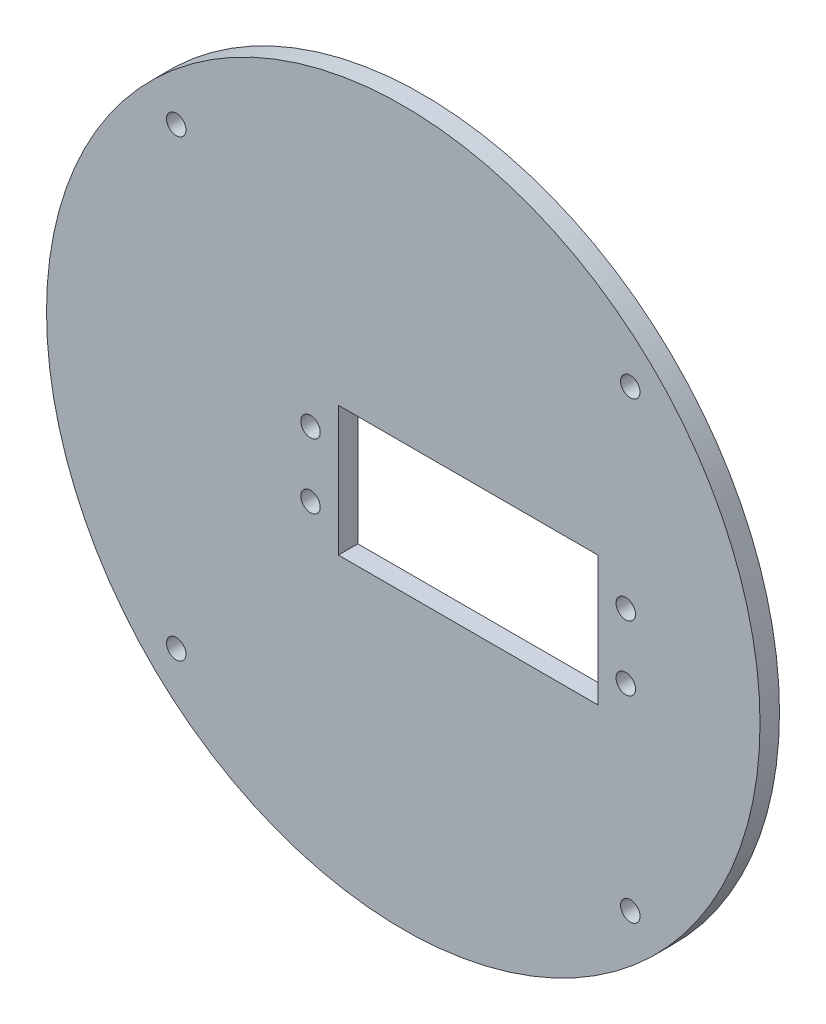
SolidWorks part; units mm, degrees
ref_plane "前视基准面" through (0, 0, 0) normal (0, 0, 1) x (1, 0, 0)
ref_plane "上视基准面" through (0, 0, 0) normal (0, 1, 0) x (1, 0, 0)
ref_plane "右视基准面" through (0, 0, 0) normal (1, 0, 0) x (0, 0, -1)
sketch "草图1" plane through (0, 0, 0) normal (0, 0, 1) x (1, 0, 0)
  line L0 (-35, -35) -> (35, -35)
  line L1 (-35, -35) -> (-35, 35)
  line L2 (-35, 35) -> (35, 35)
  line L3 (35, -35) -> (35, 35)
  line L4 (-35, -35) -> (35, 35) construction
  line L5 (-35, 35) -> (35, -35) construction
  line L7 (-10, 10) -> (30, 10)
  line L8 (-10, 10) -> (-10, -10)
  line L9 (-10, -10) -> (30, -10)
  line L10 (30, 10) -> (30, -10)
  line L11 (-14.3, 5) -> (34.3, 5)
  line L12 (-14.3, 5) -> (-14.3, -5)
  line L13 (-14.3, -5) -> (34.3, -5)
  line L14 (34.3, 5) -> (34.3, -5)
  circle A0 centre (0, 0) radius 55
  circle A1 centre (0, 0) radius 45
  circle A2 centre (-35, 35) radius 1.5
  circle A3 centre (35, 35) radius 1.5
  circle A4 centre (35, -35) radius 1.5
  circle A5 centre (-35, -35) radius 1.5
  circle A6 centre (-14.3, 5) radius 1.5
  circle A7 centre (-14.3, -5) radius 1.5
  circle A8 centre (34.3, 5) radius 1.5
  circle A9 centre (34.3, -5) radius 1.5
  point P16 (-10, 0)
  point P21 (-14.3, 0)
  point P22 (10, 5)
  point P23 (10, 10)
  dimension "D1" = 90
  dimension "D3" = 3
  dimension "D4" = 3
  dimension "D5" = 3
  dimension "D6" = 3
  dimension "D7" = 110
  dimension "D14" = 3
  dimension "D15" = 3
  dimension "D16" = 3
  dimension "D17" = 3
  dimension "D2" = 70
  dimension "D8" = 70
  dimension "D9" = 40
  dimension "D10" = 20
  dimension "D11" = 10
  dimension "D12" = 4.3
  dimension "D13" = 10
extrude "凸台-拉伸2" add sketch "草图1" along normal blind 3 contours A0 A5 L1 A1 A2 L2 A3 L3 A4 L0 | L1 A1 | A9 L13 L10 L9 L8 A7 L12 A6 L11 L7 A8 L3 A1 L2 L1 L0 | L2 A1 | A3 L2 A1 L3 | A9 L3 A1 A8 | L0 A1 | A5 L0 A1 L1 | A7 L13 L8 L11 A6 L12 | A2 L1 A1 L2 | A4 L3 A1 L0 | A9 L14 A8 L11 L10 L13 | A9 L3 A8 L14
